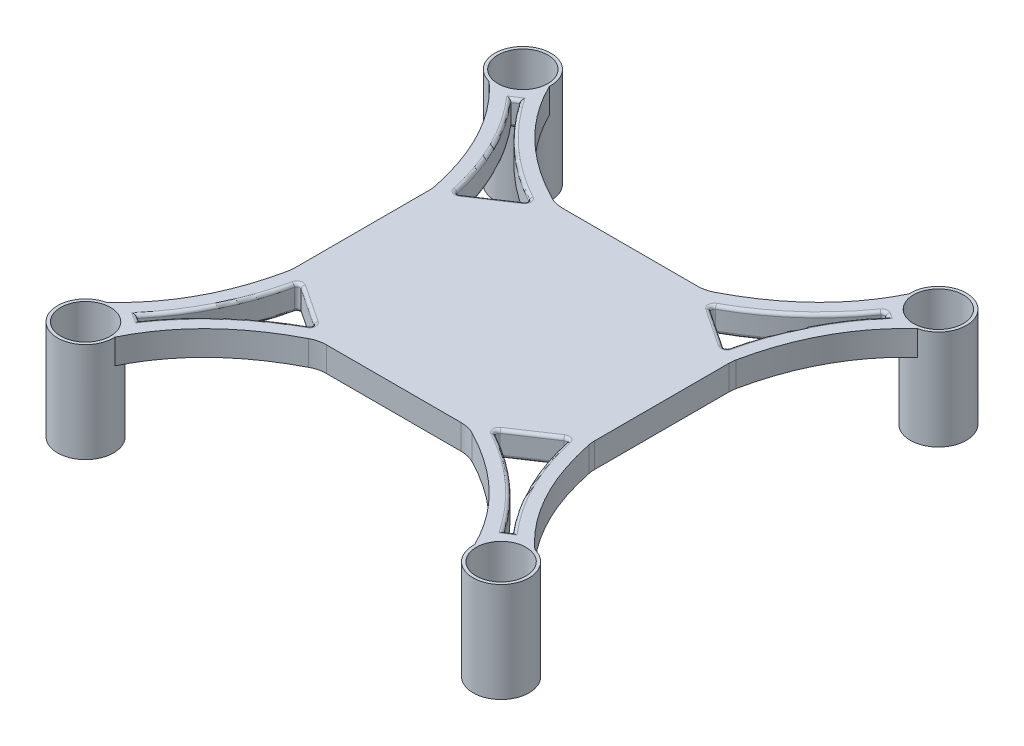
SolidWorks part; units mm, degrees
ref_plane "Front Plane" through (0, 0, 0) normal (0, 0, 1) x (1, 0, 0)
ref_plane "Top Plane" through (0, 0, 0) normal (0, 1, 0) x (1, 0, 0)
ref_plane "Right Plane" through (0, 0, 0) normal (1, 0, 0) x (0, 0, -1)
sketch "Sketch1" plane through (0, 0, 0) normal (0, 1, 0) x (1, 0, 0)
  line L0 (0, 48.6138) -> (0, -54.4719) construction
  line L1 (-10.8164, 24.6879) -> (10.8164, 24.6879)
  line L2 (46.7137, 5.7094) -> (-47.0237, 5.7094) construction
  line L3 (24.068, 16.5258) -> (24.068, -5.1069)
  line L4 (-10.8164, -13.269) -> (10.8164, -13.269)
  line L5 (-24.068, 16.5258) -> (-24.068, -5.1069)
  circle A0 centre (33.37, 40.8271) radius 4
  arc A1 (13.1162, 25.2482) -> (10.8164, 24.6879) centre (10.8164, 29.6879) cw
  arc A2 (24.1737, 17.5483) -> (24.068, 16.5258) centre (29.068, 16.5258) ccw
  arc A3 (24.1737, -6.1295) -> (24.068, -5.1069) centre (29.068, -5.1069) cw
  circle A4 centre (33.37, -29.4083) radius 4
  arc A5 (13.1162, -13.8293) -> (10.8164, -13.269) centre (10.8164, -18.269) ccw
  arc A6 (-13.1162, 25.2482) -> (-10.8164, 24.6879) centre (-10.8164, 29.6879) ccw
  arc A7 (-13.1162, -13.8293) -> (-10.8164, -13.269) centre (-10.8164, -18.269) cw
  circle A8 centre (-33.37, -29.4083) radius 4
  circle A9 centre (-33.37, 40.8271) radius 4
  arc A10 (-24.1737, 17.5483) -> (-24.068, 16.5258) centre (-29.068, 16.5258) cw
  arc A11 (-24.1737, -6.1295) -> (-24.068, -5.1069) centre (-29.068, -5.1069) ccw
  spline S0 degree 3 poles (13.1162, 25.2482) (17.1244, 27.3245) (23.8928, 32.2537) (28.1654, 38.7361) (29.6777, 42.3656) knots 0.037225 0.037225 0.037225 0.037225 0.443973 0.850721 0.850721 0.850721 0.850721
  spline S1 degree 3 poles (24.1737, 17.5483) (25.0548, 21.7657) (27.8837, 29.4488) (32.8158, 35.2456) (35.8785, 37.7115) knots 0.053222 0.053222 0.053222 0.053222 0.443973 0.850721 0.850721 0.850721 0.850721
  spline S2 degree 3 poles (24.1737, -6.1295) (25.0548, -10.3468) (27.8837, -18.0299) (32.8158, -23.8267) (35.8785, -26.2926) knots 0.053222 0.053222 0.053222 0.053222 0.443973 0.850721 0.850721 0.850721 0.850721
  spline S3 degree 3 poles (13.1162, -13.8293) (17.1244, -15.9056) (23.8928, -20.8348) (28.1654, -27.3172) (29.6777, -30.9467) knots 0.037225 0.037225 0.037225 0.037225 0.443973 0.850721 0.850721 0.850721 0.850721
  spline S4 degree 3 poles (-13.1162, -13.8293) (-17.1244, -15.9056) (-23.8928, -20.8348) (-28.1654, -27.3172) (-29.6777, -30.9467) knots 0.037225 0.037225 0.037225 0.037225 0.443973 0.850721 0.850721 0.850721 0.850721
  spline S5 degree 3 poles (-24.1737, -6.1295) (-25.0548, -10.3468) (-27.8837, -18.0299) (-32.8158, -23.8267) (-35.8785, -26.2926) knots 0.053222 0.053222 0.053222 0.053222 0.443973 0.850721 0.850721 0.850721 0.850721
  spline S6 degree 3 poles (-24.1737, 17.5483) (-25.0548, 21.7657) (-27.8837, 29.4488) (-32.8158, 35.2456) (-35.8785, 37.7115) knots 0.053222 0.053222 0.053222 0.053222 0.443973 0.850721 0.850721 0.850721 0.850721
  spline S7 degree 3 poles (-13.1162, 25.2482) (-17.1244, 27.3245) (-23.8928, 32.2537) (-28.1654, 38.7361) (-29.6777, 42.3656) knots 0.037225 0.037225 0.037225 0.037225 0.443973 0.850721 0.850721 0.850721 0.850721
  point P19 (24.068, 5.7094)
  point P37 (0, -13.269)
  point P54 (0, 24.6879)
  point P56 (0, 24.6879)
  dimension "D2" = 5
  dimension "D1" = 5
extrude "Boss-Extrude3" add sketch "Sketch1" along normal blind 4 contours A6 S7 A9 S6 A10 L5 A11 S5 A8 S4 A7 L4 A5 S3 A4 S2 A3 L3 A2 S1 A0 S0 A1 L1 | A4 | A8
sketch "Sketch5" plane through (0, 4, 0) normal (0, 1, 0) x (1, 0, 0)
  line L8 (30.1977, 35.734) -> (29.3225, 36.2906)
  line L9 (14.2661, 23.0284) -> (21.7265, 18.0596)
  line L10 (0, 31.6796) -> (0, -34.2074) construction
  line L11 (-56.7161, 5.7094) -> (61.3158, 5.7094) construction
  line L12 (-21.568, 16.5258) -> (-21.568, -5.1069)
  line L13 (-10.8164, -10.769) -> (10.8164, -10.769)
  line L14 (21.568, -5.1069) -> (21.568, 16.5258)
  line L15 (10.8164, 22.1879) -> (-10.8164, 22.1879)
  line L16 (-21.568, 16.5258) -> (-21.568, -5.1069)
  line L17 (-10.8164, -10.769) -> (10.8164, -10.769)
  line L18 (21.568, -5.1069) -> (21.568, 16.5258)
  line L19 (10.8164, 22.1879) -> (-10.8164, 22.1879)
  line L20 (-30.1977, 35.734) -> (-29.3225, 36.2906)
  line L21 (-14.2661, 23.0284) -> (-21.7265, 18.0596)
  line L22 (30.1977, -24.3151) -> (29.3225, -24.8718)
  line L23 (14.2661, -11.6095) -> (21.7265, -6.6407)
  line L24 (-14.2661, -11.6095) -> (-21.7265, -6.6407)
  line L25 (-30.1977, -24.3151) -> (-29.3225, -24.8718)
  arc A24 (21.7265, 18.0596) -> (30.1977, 35.734) centre (59.9069, 10.6274) cw
  arc A25 (14.2661, 23.0284) -> (29.3225, 36.2906) centre (-4.8209, 59.8754) ccw
  arc A26 (-14.2661, 23.0284) -> (-29.3225, 36.2906) centre (4.8209, 59.8754) cw
  arc A27 (-21.7265, 18.0596) -> (-30.1977, 35.734) centre (-59.9069, 10.6274) ccw
  arc A28 (21.7265, -6.6407) -> (30.1977, -24.3151) centre (59.9069, 0.7914) ccw
  arc A29 (14.2661, -11.6095) -> (29.3225, -24.8718) centre (-4.8209, -48.4565) cw
  arc A30 (-21.7265, -6.6407) -> (-30.1977, -24.3151) centre (-59.9069, 0.7914) cw
  arc A31 (-14.2661, -11.6095) -> (-29.3225, -24.8718) centre (4.8209, -48.4565) ccw
  arc A36 (-14.2661, 23.0284) -> (-10.8164, 22.1879) centre (-10.8164, 29.6879) ccw
  arc A37 (-31.9854, 41.404) -> (-34.3107, 39.6587) centre (-33.37, 40.8271) ccw
  arc A38 (-21.568, 16.5258) -> (-21.7265, 18.0596) centre (-29.068, 16.5258) ccw
  arc A39 (-21.7265, -6.6407) -> (-21.568, -5.1069) centre (-29.068, -5.1069) ccw
  arc A40 (-34.3107, -28.2399) -> (-31.9854, -29.9852) centre (-33.37, -29.4083) ccw
  arc A41 (-10.8164, -10.769) -> (-14.2661, -11.6095) centre (-10.8164, -18.269) ccw
  arc A42 (14.2661, -11.6095) -> (10.8164, -10.769) centre (10.8164, -18.269) ccw
  arc A43 (31.9854, -29.9852) -> (34.3107, -28.2399) centre (33.37, -29.4083) ccw
  arc A44 (21.568, -5.1069) -> (21.7265, -6.6407) centre (29.068, -5.1069) ccw
  arc A45 (21.7265, 18.0596) -> (21.568, 16.5258) centre (29.068, 16.5258) ccw
  arc A46 (34.3107, 39.6587) -> (31.9854, 41.404) centre (33.37, 40.8271) ccw
  arc A47 (10.8164, 22.1879) -> (14.2661, 23.0284) centre (10.8164, 29.6879) ccw
  arc A48 (-14.2661, 23.0284) -> (-10.8164, 22.1879) centre (-10.8164, 29.6879) ccw
  arc A49 (-31.9854, 41.404) -> (-34.3107, 39.6587) centre (-33.37, 40.8271) ccw
  arc A50 (-21.568, 16.5258) -> (-21.7265, 18.0596) centre (-29.068, 16.5258) ccw
  arc A51 (-21.7265, -6.6407) -> (-21.568, -5.1069) centre (-29.068, -5.1069) ccw
  arc A52 (-34.3107, -28.2399) -> (-31.9854, -29.9852) centre (-33.37, -29.4083) ccw
  arc A53 (-10.8164, -10.769) -> (-14.2661, -11.6095) centre (-10.8164, -18.269) ccw
  arc A54 (14.2661, -11.6095) -> (10.8164, -10.769) centre (10.8164, -18.269) ccw
  arc A55 (31.9854, -29.9852) -> (34.3107, -28.2399) centre (33.37, -29.4083) ccw
  arc A56 (21.568, -5.1069) -> (21.7265, -6.6407) centre (29.068, -5.1069) ccw
  arc A57 (21.7265, 18.0596) -> (21.568, 16.5258) centre (29.068, 16.5258) ccw
  arc A58 (34.3107, 39.6587) -> (31.9854, 41.404) centre (33.37, 40.8271) ccw
  arc A59 (10.8164, 22.1879) -> (14.2661, 23.0284) centre (10.8164, 29.6879) ccw
  spline S24 degree 3 poles (-1293.2283, -2676.1936) (402.9954, 283.6964) (71.687, -39.0407) (-20.733, 27.0608) (-21.5941, 27.7299) (-23.2451, 29.1291) (-24.0372, 29.8607) (-26.3082, 32.1572) (-27.6818, 33.823) (-29.5062, 36.5488) (-30.0686, 37.4862) (-148.6105, 258.9601) (2211.5543, 1795.9862) (-2829.0833, -598.5842) knots -12.641044 -12.641044 -12.641044 -12.641044 0.25 0.25 0.375 0.375 0.5 0.5 0.75 0.75 0.875 0.875 29.563011 29.563011 29.563011 29.563011 only from (-14.2661, 23.0284) to (-31.9854, 41.404)
  spline S25 degree 3 poles (184.4367, 1294.6818) (-2287.7745, -1535.7828) (-189.055, 223.3772) (-29.3932, 34.7953) (-29.0569, 34.3781) (-28.4081, 33.5326) (-28.0949, 33.1036) (-27.1878, 31.798) (-26.6265, 30.9032) (-25.5858, 29.0674) (-25.1064, 28.1263) (-24.2254, 26.2004) (-23.8232, 25.2138) (14.8609, -81.4612) (-389.7731, -313.9027) (2922.9923, 517.5478) knots -28.611005 -28.611005 -28.611005 -28.611005 0.25 0.25 0.3125 0.3125 0.375 0.375 0.5 0.5 0.625 0.625 0.75 0.75 13.911662 13.911662 13.911662 13.911662 only from (-34.3107, 39.6587) to (-21.7265, 18.0596)
  spline S26 degree 3 poles (2921.1119, -516.4542) (-391.9018, 328.5971) (14.9929, 93.228) (-23.8239, -13.7968) (-24.2273, -14.786) (-25.109, -16.7127) (-25.5883, -17.6532) (-27.1475, -20.403) (-28.3481, -22.1405) (-30.0728, -24.1795) (-30.4289, -24.5805) (-31.1575, -25.3621) (-31.5307, -25.7436) (-200.6034, -190.4869) (-2092.5502, 1439.1475) (1401.2137, -2538.0416) knots -12.9551 -12.9551 -12.9551 -12.9551 0.25 0.25 0.375 0.375 0.5 0.5 0.75 0.75 0.8125 0.8125 0.875 0.875 28.469753 28.469753 28.469753 28.469753 only from (-21.7265, -6.6407) to (-34.3107, -28.2399)
  spline S27 degree 3 poles (-1299.9106, -167.3195) (2099.0764, -1746.164) (-165.6783, -228.7682) (-28.6026, -23.7794) (-28.2872, -23.3321) (-27.6386, -22.4581) (-27.3048, -22.0305) (-26.2754, -20.7747) (-25.5522, -19.9738) (-24.0357, -18.4404) (-23.2425, -17.7079) (-21.5899, -16.3076) (-20.7278, -15.6381) (71.893, 50.5892) (405.3389, -272.9519) (-1299.2596, 2684.5757) knots -27.923103 -27.923103 -27.923103 -27.923103 0.25 0.25 0.3125 0.3125 0.375 0.375 0.5 0.5 0.625 0.625 0.75 0.75 13.681261 13.681261 13.681261 13.681261 only from (-31.9854, -29.9852) to (-14.2661, -11.6095)
  spline S28 degree 3 poles (1293.2283, 2687.6124) (-402.9954, -272.2775) (-71.687, 50.4595) (20.733, -15.6419) (21.5941, -16.311) (23.2451, -17.7102) (24.0372, -18.4419) (26.3082, -20.7383) (27.6818, -22.4042) (29.5062, -25.1299) (30.0686, -26.0673) (148.6105, -247.5412) (-2211.5543, -1784.5673) (2829.0833, 610.0031) knots -12.641044 -12.641044 -12.641044 -12.641044 0.25 0.25 0.375 0.375 0.5 0.5 0.75 0.75 0.875 0.875 29.563011 29.563011 29.563011 29.563011 only from (14.2661, -11.6095) to (31.9854, -29.9852)
  spline S29 degree 3 poles (-184.4367, -1283.2629) (2287.7745, 1547.2017) (189.055, -211.9583) (29.3932, -23.3765) (29.0569, -22.9592) (28.4081, -22.1137) (28.0949, -21.6847) (27.1878, -20.3792) (26.6265, -19.4843) (25.5858, -17.6485) (25.1064, -16.7074) (24.2254, -14.7815) (23.8232, -13.7949) (-14.8609, 92.88) (389.7731, 325.3216) (-2922.9923, -506.1289) knots -28.611005 -28.611005 -28.611005 -28.611005 0.25 0.25 0.3125 0.3125 0.375 0.375 0.5 0.5 0.625 0.625 0.75 0.75 13.911662 13.911662 13.911662 13.911662 only from (34.3107, -28.2399) to (21.7265, -6.6407)
  spline S30 degree 3 poles (-2921.1119, 527.8731) (391.9018, -317.1782) (-14.9929, -81.8091) (23.8239, 25.2157) (24.2273, 26.2049) (25.109, 28.1316) (25.5883, 29.0721) (27.1475, 31.8218) (28.3481, 33.5593) (30.0728, 35.5984) (30.4289, 35.9994) (31.1575, 36.781) (31.5307, 37.1625) (200.6034, 201.9057) (2092.5502, -1427.7286) (-1401.2137, 2549.4604) knots -12.9551 -12.9551 -12.9551 -12.9551 0.25 0.25 0.375 0.375 0.5 0.5 0.75 0.75 0.8125 0.8125 0.875 0.875 28.469753 28.469753 28.469753 28.469753 only from (21.7265, 18.0596) to (34.3107, 39.6587)
  spline S31 degree 3 poles (1299.9106, 178.7384) (-2099.0764, 1757.5829) (165.6783, 240.187) (28.6026, 35.1983) (28.2872, 34.7509) (27.6386, 33.877) (27.3048, 33.4493) (26.2754, 32.1936) (25.5522, 31.3927) (24.0357, 29.8593) (23.2425, 29.1267) (21.5899, 27.7265) (20.7278, 27.0569) (-71.893, -39.1703) (-405.3389, 284.3708) (1299.2596, -2673.1568) knots -27.923103 -27.923103 -27.923103 -27.923103 0.25 0.25 0.3125 0.3125 0.375 0.375 0.5 0.5 0.625 0.625 0.75 0.75 13.681261 13.681261 13.681261 13.681261 only from (31.9854, 41.404) to (14.2661, 23.0284)
  spline S32 degree 3 poles (-14.2661, 23.0284) (-16.205, 24.0327) (-18.0703, 25.1564) (-20.733, 27.0608) (-21.5941, 27.7299) (-23.2451, 29.1291) (-24.0372, 29.8607) (-26.3082, 32.1572) (-27.6818, 33.823) (-29.5062, 36.5488) (-30.0686, 37.4862) (-31.0971, 39.4078) (-31.5644, 40.3937) (-31.9854, 41.404) knots 0 0 0 0 0.25 0.25 0.375 0.375 0.5 0.5 0.75 0.75 0.875 0.875 1 1 1 1
  spline S33 degree 3 poles (-34.3107, 39.6587) (-32.6438, 38.3167) (-31.1183, 36.8328) (-29.3932, 34.7953) (-29.0569, 34.3781) (-28.4081, 33.5326) (-28.0949, 33.1036) (-27.1878, 31.798) (-26.6265, 30.9032) (-25.5858, 29.0674) (-25.1064, 28.1263) (-24.2254, 26.2004) (-23.8232, 25.2138) (-22.7314, 22.203) (-22.1633, 20.1501) (-21.7265, 18.0596) knots 0 0 0 0 0.25 0.25 0.3125 0.3125 0.375 0.375 0.5 0.5 0.625 0.625 0.75 0.75 1 1 1 1
  spline S34 degree 3 poles (-21.7265, -6.6407) (-22.1635, -8.7325) (-22.7319, -10.786) (-23.8239, -13.7968) (-24.2273, -14.786) (-25.109, -16.7127) (-25.5883, -17.6532) (-27.1475, -20.403) (-28.3481, -22.1405) (-30.0728, -24.1795) (-30.4289, -24.5805) (-31.1575, -25.3621) (-31.5307, -25.7436) (-32.677, -26.8605) (-33.4765, -27.5682) (-34.3107, -28.2399) knots 0 0 0 0 0.25 0.25 0.375 0.375 0.5 0.5 0.75 0.75 0.8125 0.8125 0.875 0.875 1 1 1 1
  spline S35 degree 3 poles (-31.9854, -29.9852) (-31.1443, -27.9665) (-30.1197, -26.0482) (-28.6026, -23.7794) (-28.2872, -23.3321) (-27.6386, -22.4581) (-27.3048, -22.0305) (-26.2754, -20.7747) (-25.5522, -19.9738) (-24.0357, -18.4404) (-23.2425, -17.7079) (-21.5899, -16.3076) (-20.7278, -15.6381) (-18.0676, -13.7359) (-16.2038, -12.6132) (-14.2661, -11.6095) knots 0 0 0 0 0.25 0.25 0.3125 0.3125 0.375 0.375 0.5 0.5 0.625 0.625 0.75 0.75 1 1 1 1
  spline S36 degree 3 poles (14.2661, -11.6095) (16.205, -12.6139) (18.0703, -13.7375) (20.733, -15.6419) (21.5941, -16.311) (23.2451, -17.7102) (24.0372, -18.4419) (26.3082, -20.7383) (27.6818, -22.4042) (29.5062, -25.1299) (30.0686, -26.0673) (31.0971, -27.989) (31.5644, -28.9748) (31.9854, -29.9852) knots 0 0 0 0 0.25 0.25 0.375 0.375 0.5 0.5 0.75 0.75 0.875 0.875 1 1 1 1
  spline S37 degree 3 poles (34.3107, -28.2399) (32.6438, -26.8979) (31.1183, -25.414) (29.3932, -23.3765) (29.0569, -22.9592) (28.4081, -22.1137) (28.0949, -21.6847) (27.1878, -20.3792) (26.6265, -19.4843) (25.5858, -17.6485) (25.1064, -16.7074) (24.2254, -14.7815) (23.8232, -13.7949) (22.7314, -10.7842) (22.1633, -8.7312) (21.7265, -6.6407) knots 0 0 0 0 0.25 0.25 0.3125 0.3125 0.375 0.375 0.5 0.5 0.625 0.625 0.75 0.75 1 1 1 1
  spline S38 degree 3 poles (21.7265, 18.0596) (22.1635, 20.1513) (22.7319, 22.2049) (23.8239, 25.2157) (24.2273, 26.2049) (25.109, 28.1316) (25.5883, 29.0721) (27.1475, 31.8218) (28.3481, 33.5593) (30.0728, 35.5984) (30.4289, 35.9994) (31.1575, 36.781) (31.5307, 37.1625) (32.677, 38.2793) (33.4765, 38.9871) (34.3107, 39.6587) knots 0 0 0 0 0.25 0.25 0.375 0.375 0.5 0.5 0.75 0.75 0.8125 0.8125 0.875 0.875 1 1 1 1
  spline S39 degree 3 poles (31.9854, 41.404) (31.1443, 39.3854) (30.1197, 37.467) (28.6026, 35.1983) (28.2872, 34.7509) (27.6386, 33.877) (27.3048, 33.4493) (26.2754, 32.1936) (25.5522, 31.3927) (24.0357, 29.8593) (23.2425, 29.1267) (21.5899, 27.7265) (20.7278, 27.0569) (18.0676, 25.1548) (16.2038, 24.0321) (14.2661, 23.0284) knots 0 0 0 0 0.25 0.25 0.3125 0.3125 0.375 0.375 0.5 0.5 0.625 0.625 0.75 0.75 1 1 1 1
  dimension "D2" = 6
  dimension "D1" = 2.5
extrude "Cut-Extrude3" cut sketch "Sketch5" against normal blind 4 contours A27 L20 A26 L21 | A31 L25 A30 L24 | A29 L22 A28 L23 | L9 A24 L8 A25
sketch "Sketch7" plane through (0, 4, 0) normal (0, 1, 0) x (1, 0, 0)
  line L0 (0, 39.7075) -> (0, -36.8004) construction
  line L1 (24.068, 5.7094) -> (-40.5042, 5.7094) construction
  line L4 (-24.068, 16.5258) -> (-24.068, -5.1069)
  line L5 (-10.8164, -13.269) -> (10.8164, -13.269)
  line L6 (24.068, -5.1069) -> (24.068, 16.5258)
  line L7 (10.8164, 24.6879) -> (-10.8164, 24.6879)
  line L8 (-24.068, 16.5258) -> (-24.068, -5.1069)
  line L9 (-10.8164, -13.269) -> (10.8164, -13.269)
  line L10 (24.068, -5.1069) -> (24.068, 16.5258)
  line L11 (10.8164, 24.6879) -> (-10.8164, 24.6879)
  circle A0 centre (33.37, 40.8271) radius 4.5
  circle A1 centre (-33.37, 40.8271) radius 4.5
  circle A2 centre (33.37, -29.4083) radius 4.5
  circle A3 centre (-33.37, -29.4083) radius 4.5
  arc A12 (-13.1162, 25.2482) -> (-10.8164, 24.6879) centre (-10.8164, 29.6879) ccw
  arc A13 (-29.6777, 42.3656) -> (-35.8785, 37.7115) centre (-33.37, 40.8271) ccw
  arc A14 (-24.068, 16.5258) -> (-24.1737, 17.5483) centre (-29.068, 16.5258) ccw
  arc A15 (-24.1737, -6.1295) -> (-24.068, -5.1069) centre (-29.068, -5.1069) ccw
  arc A16 (-35.8785, -26.2926) -> (-29.6777, -30.9467) centre (-33.37, -29.4083) ccw
  arc A17 (-10.8164, -13.269) -> (-13.1162, -13.8293) centre (-10.8164, -18.269) ccw
  arc A18 (13.1162, -13.8293) -> (10.8164, -13.269) centre (10.8164, -18.269) ccw
  arc A19 (29.6777, -30.9467) -> (35.8785, -26.2926) centre (33.37, -29.4083) ccw
  arc A20 (24.068, -5.1069) -> (24.1737, -6.1295) centre (29.068, -5.1069) ccw
  arc A21 (24.1737, 17.5483) -> (24.068, 16.5258) centre (29.068, 16.5258) ccw
  arc A22 (35.8785, 37.7115) -> (29.6777, 42.3656) centre (33.37, 40.8271) ccw
  arc A23 (10.8164, 24.6879) -> (13.1162, 25.2482) centre (10.8164, 29.6879) ccw
  arc A24 (-13.1162, 25.2482) -> (-10.8164, 24.6879) centre (-10.8164, 29.6879) ccw
  arc A26 (-24.068, 16.5258) -> (-24.1737, 17.5483) centre (-29.068, 16.5258) ccw
  arc A27 (-24.1737, -6.1295) -> (-24.068, -5.1069) centre (-29.068, -5.1069) ccw
  arc A29 (-10.8164, -13.269) -> (-13.1162, -13.8293) centre (-10.8164, -18.269) ccw
  arc A30 (13.1162, -13.8293) -> (10.8164, -13.269) centre (10.8164, -18.269) ccw
  arc A32 (24.068, -5.1069) -> (24.1737, -6.1295) centre (29.068, -5.1069) ccw
  arc A33 (24.1737, 17.5483) -> (24.068, 16.5258) centre (29.068, 16.5258) ccw
  arc A35 (10.8164, 24.6879) -> (13.1162, 25.2482) centre (10.8164, 29.6879) ccw
  spline S8 degree 3 poles (2720.72, 1244.7307) (991.1455, 333.5721) (-865.7115, -486.6483) (635.9303, 783.1648) (2262.5906, 1965.6024) knots -14.255308 -14.255308 -14.255308 -14.255308 0.443973 15.5857 15.5857 15.5857 15.5857 only from (-13.1162, 25.2482) to (-29.6777, 42.3656)
  spline S9 degree 3 poles (-2522.8628, -1626.2016) (-933.1195, -394.5106) (705.5357, 692.6861) (-600.5192, -861.0366) (-1958.2843, -2267.0883) knots -14.68191 -14.68191 -14.68191 -14.68191 0.45997 15.158154 15.158154 15.158154 15.158154 only from (-35.8785, 37.7115) to (-24.1737, 17.5483)
  spline S10 degree 3 poles (-1958.2964, 2278.5196) (-600.523, 872.46) (705.5374, -681.2679) (-933.1178, 405.9283) (-2522.8577, 1637.6166) knots -14.254254 -14.254254 -14.254254 -14.254254 0.443973 15.585837 15.585837 15.585837 15.585837 only from (-24.1737, -6.1295) to (-35.8785, -26.2926)
  spline S11 degree 3 poles (2262.6173, -1954.203) (635.9387, -771.753) (-865.7103, 498.064) (991.1298, -322.1462) (2720.6752, -1233.2882) knots -14.697836 -14.697836 -14.697836 -14.697836 0.443973 15.143128 15.143128 15.143128 15.143128 only from (-29.6777, -30.9467) to (-13.1162, -13.8293)
  spline S12 degree 3 poles (-2720.72, -1233.3118) (-991.1455, -322.1532) (865.7115, 498.0671) (-635.9303, -771.746) (-2262.5906, -1954.1835) knots -14.255308 -14.255308 -14.255308 -14.255308 0.443973 15.5857 15.5857 15.5857 15.5857 only from (13.1162, -13.8293) to (29.6777, -30.9467)
  spline S13 degree 3 poles (2522.8628, 1637.6205) (933.1195, 405.9294) (-705.5357, -681.2672) (600.5192, 872.4554) (1958.2843, 2278.5072) knots -14.68191 -14.68191 -14.68191 -14.68191 0.45997 15.158154 15.158154 15.158154 15.158154 only from (35.8785, -26.2926) to (24.1737, -6.1295)
  spline S14 degree 3 poles (1958.2964, -2267.1008) (600.523, -861.0411) (-705.5374, 692.6868) (933.1178, -394.5094) (2522.8577, -1626.1977) knots -14.254254 -14.254254 -14.254254 -14.254254 0.443973 15.585837 15.585837 15.585837 15.585837 only from (24.1737, 17.5483) to (35.8785, 37.7115)
  spline S15 degree 3 poles (-2262.6173, 1965.6218) (-635.9387, 783.1719) (865.7103, -486.6451) (-991.1298, 333.5651) (-2720.6752, 1244.7071) knots -14.697836 -14.697836 -14.697836 -14.697836 0.443973 15.143128 15.143128 15.143128 15.143128 only from (29.6777, 42.3656) to (13.1162, 25.2482)
  spline S16 degree 3 poles (-13.1162, 25.2482) (-17.1244, 27.3245) (-23.8928, 32.2537) (-28.1654, 38.7361) (-29.6777, 42.3656) knots 0.037225 0.037225 0.037225 0.037225 0.443973 0.850721 0.850721 0.850721 0.850721
  spline S17 degree 3 poles (-35.8785, 37.7115) (-32.8158, 35.2456) (-27.8837, 29.4488) (-25.0548, 21.7657) (-24.1737, 17.5483) knots 0.053222 0.053222 0.053222 0.053222 0.45997 0.850721 0.850721 0.850721 0.850721
  spline S18 degree 3 poles (-24.1737, -6.1295) (-25.0548, -10.3468) (-27.8837, -18.0299) (-32.8158, -23.8267) (-35.8785, -26.2926) knots 0.053222 0.053222 0.053222 0.053222 0.443973 0.850721 0.850721 0.850721 0.850721
  spline S19 degree 3 poles (-29.6777, -30.9467) (-28.1654, -27.3172) (-23.8928, -20.8348) (-17.1244, -15.9056) (-13.1162, -13.8293) knots 0.037225 0.037225 0.037225 0.037225 0.443973 0.850721 0.850721 0.850721 0.850721
  spline S20 degree 3 poles (13.1162, -13.8293) (17.1244, -15.9056) (23.8928, -20.8348) (28.1654, -27.3172) (29.6777, -30.9467) knots 0.037225 0.037225 0.037225 0.037225 0.443973 0.850721 0.850721 0.850721 0.850721
  spline S21 degree 3 poles (35.8785, -26.2926) (32.8158, -23.8267) (27.8837, -18.0299) (25.0548, -10.3468) (24.1737, -6.1295) knots 0.053222 0.053222 0.053222 0.053222 0.45997 0.850721 0.850721 0.850721 0.850721
  spline S22 degree 3 poles (24.1737, 17.5483) (25.0548, 21.7657) (27.8837, 29.4488) (32.8158, 35.2456) (35.8785, 37.7115) knots 0.053222 0.053222 0.053222 0.053222 0.443973 0.850721 0.850721 0.850721 0.850721
  spline S23 degree 3 poles (29.6777, 42.3656) (28.1654, 38.7361) (23.8928, 32.2537) (17.1244, 27.3245) (13.1162, 25.2482) knots 0.037225 0.037225 0.037225 0.037225 0.443973 0.850721 0.850721 0.850721 0.850721
  dimension "D1" = 0
extrude "Cut-Extrude5" cut sketch "Sketch7" against normal blind 4 contours A0 | A2 | A3 | A1
sketch "Sketch9" plane through (0, 4, 0) normal (0, 1, 0) x (1, 0, 0)
  line L0 (0, 27.8112) -> (0, -19.6156) construction
  line L1 (-24.068, 5.7094) -> (24.068, 5.7094) construction
  line L4 (24.068, -5.1069) -> (24.068, 16.5258)
  line L5 (10.8164, 24.6879) -> (-10.8164, 24.6879)
  line L6 (-24.068, 16.5258) -> (-24.068, -5.1069)
  line L7 (-10.8164, -13.269) -> (10.8164, -13.269)
  line L8 (24.068, -5.1069) -> (24.068, 16.5258)
  line L9 (10.8164, 24.6879) -> (-10.8164, 24.6879)
  line L10 (-24.068, 16.5258) -> (-24.068, -5.1069)
  line L11 (-10.8164, -13.269) -> (10.8164, -13.269)
  circle A0 centre (33.37, 40.8271) radius 4.5
  circle A1 centre (-33.37, 40.8271) radius 4.5
  circle A2 centre (33.37, -29.4083) radius 4.5
  circle A3 centre (-33.37, -29.4083) radius 4.5
  arc A12 (34.4034, -25.0285) -> (28.8759, -29.1773) centre (33.37, -29.4083) ccw
  arc A13 (24.068, -5.1069) -> (24.1737, -6.1295) centre (29.068, -5.1069) ccw
  arc A14 (24.1737, 17.5483) -> (24.068, 16.5258) centre (29.068, 16.5258) ccw
  arc A15 (28.8759, 40.5962) -> (34.4034, 36.4474) centre (33.37, 40.8271) ccw
  arc A16 (10.8164, 24.6879) -> (13.1162, 25.2482) centre (10.8164, 29.6879) ccw
  arc A17 (-13.1162, 25.2482) -> (-10.8164, 24.6879) centre (-10.8164, 29.6879) ccw
  arc A18 (-34.4034, 36.4474) -> (-28.8759, 40.5962) centre (-33.37, 40.8271) ccw
  arc A19 (-24.068, 16.5258) -> (-24.1737, 17.5483) centre (-29.068, 16.5258) ccw
  arc A20 (-24.1737, -6.1295) -> (-24.068, -5.1069) centre (-29.068, -5.1069) ccw
  arc A21 (-28.8759, -29.1773) -> (-34.4034, -25.0285) centre (-33.37, -29.4083) ccw
  arc A22 (-10.8164, -13.269) -> (-13.1162, -13.8293) centre (-10.8164, -18.269) ccw
  arc A23 (13.1162, -13.8293) -> (10.8164, -13.269) centre (10.8164, -18.269) ccw
  arc A24 (34.4034, -25.0285) -> (28.8759, -29.1773) centre (33.37, -29.4083) ccw
  arc A25 (24.068, -5.1069) -> (24.1737, -6.1295) centre (29.068, -5.1069) ccw
  arc A26 (24.1737, 17.5483) -> (24.068, 16.5258) centre (29.068, 16.5258) ccw
  arc A27 (28.8759, 40.5962) -> (34.4034, 36.4474) centre (33.37, 40.8271) ccw
  arc A28 (10.8164, 24.6879) -> (13.1162, 25.2482) centre (10.8164, 29.6879) ccw
  arc A29 (-13.1162, 25.2482) -> (-10.8164, 24.6879) centre (-10.8164, 29.6879) ccw
  arc A30 (-34.4034, 36.4474) -> (-28.8759, 40.5962) centre (-33.37, 40.8271) ccw
  arc A31 (-24.068, 16.5258) -> (-24.1737, 17.5483) centre (-29.068, 16.5258) ccw
  arc A32 (-24.1737, -6.1295) -> (-24.068, -5.1069) centre (-29.068, -5.1069) ccw
  arc A33 (-28.8759, -29.1773) -> (-34.4034, -25.0285) centre (-33.37, -29.4083) ccw
  arc A34 (-10.8164, -13.269) -> (-13.1162, -13.8293) centre (-10.8164, -18.269) ccw
  arc A35 (13.1162, -13.8293) -> (10.8164, -13.269) centre (10.8164, -18.269) ccw
  spline S8 degree 3 poles (-5357.2757, -2664.1702) (-1912.2513, -755.434) (1713.0976, 1025.3533) (-1409.4863, -1393.1775) (-4710.1146, -3687.3644) knots -20.481796 -20.481796 -20.481796 -20.481796 0.443973 21.81683 21.81683 21.81683 21.81683 only from (13.1162, -13.8293) to (28.8759, -29.1773)
  spline S9 degree 3 poles (4870.7441, 3503.7181) (1745.9021, 975.1515) (-1448.5159, -1347.6569) (1273.7999, 1635.8688) (4068.5259, 4410.4332) knots -20.980454 -20.980454 -20.980454 -20.980454 0.392682 21.317512 21.317512 21.317512 21.317512 only from (34.4034, -25.0285) to (24.1737, -6.1295)
  spline S10 degree 3 poles (4068.6562, -4399.1437) (1273.8418, -1624.4958) (-1448.5206, 1359.0719) (1745.8553, -963.6987) (4870.6084, -3492.1894) knots -20.481182 -20.481182 -20.481182 -20.481182 0.443973 21.8168 21.8168 21.8168 21.8168 only from (24.1737, 17.5483) to (34.4034, 36.4474)
  spline S11 degree 3 poles (-4710.1672, 3698.8198) (-1409.5031, 1404.6094) (1713.0992, -1013.933) (-1912.2325, 766.8437) (-5357.2216, 2675.5592) knots -20.996285 -20.996285 -20.996285 -20.996285 0.376685 21.302345 21.302345 21.302345 21.302345 only from (28.8759, 40.5962) to (13.1162, 25.2482)
  spline S12 degree 3 poles (5357.2757, 2675.5891) (1912.2513, 766.8529) (-1713.0976, -1013.9344) (1409.4863, 1404.5964) (4710.1146, 3698.7833) knots -20.481796 -20.481796 -20.481796 -20.481796 0.443973 21.81683 21.81683 21.81683 21.81683 only from (-13.1162, 25.2482) to (-28.8759, 40.5962)
  spline S13 degree 3 poles (-4870.7441, -3492.2992) (-1745.9021, -963.7327) (1448.5159, 1359.0758) (-1273.7999, -1624.4499) (-4068.5259, -4399.0143) knots -20.980454 -20.980454 -20.980454 -20.980454 0.392682 21.317512 21.317512 21.317512 21.317512 only from (-34.4034, 36.4474) to (-24.1737, 17.5483)
  spline S14 degree 3 poles (-4068.6562, 4410.5626) (-1273.8418, 1635.9147) (1448.5206, -1347.653) (-1745.8553, 975.1176) (-4870.6084, 3503.6083) knots -20.481182 -20.481182 -20.481182 -20.481182 0.443973 21.8168 21.8168 21.8168 21.8168 only from (-24.1737, -6.1295) to (-34.4034, -25.0285)
  spline S15 degree 3 poles (4710.1672, -3687.4009) (1409.5031, -1393.1905) (-1713.0992, 1025.3518) (1912.2325, -755.4248) (5357.2216, -2664.1403) knots -20.996285 -20.996285 -20.996285 -20.996285 0.376685 21.302345 21.302345 21.302345 21.302345 only from (-28.8759, -29.1773) to (-13.1162, -13.8293)
  spline S16 degree 3 poles (13.1162, -13.8293) (17.1244, -15.9056) (23.333, -20.4271) (27.4415, -26.2554) (28.8759, -29.1773) knots 0.037225 0.037225 0.037225 0.037225 0.443973 0.783433 0.783433 0.783433 0.783433
  spline S17 degree 3 poles (34.4034, -25.0285) (31.9985, -22.8351) (27.645, -17.3817) (25.0548, -10.3468) (24.1737, -6.1295) knots 0.053222 0.053222 0.053222 0.053222 0.392682 0.783433 0.783433 0.783433 0.783433
  spline S18 degree 3 poles (24.1737, 17.5483) (25.0548, 21.7657) (27.645, 28.8006) (31.9985, 34.254) (34.4034, 36.4474) knots 0.053222 0.053222 0.053222 0.053222 0.443973 0.783433 0.783433 0.783433 0.783433
  spline S19 degree 3 poles (28.8759, 40.5962) (27.4415, 37.6743) (23.333, 31.8459) (17.1244, 27.3245) (13.1162, 25.2482) knots 0.037225 0.037225 0.037225 0.037225 0.376685 0.783433 0.783433 0.783433 0.783433
  spline S20 degree 3 poles (-13.1162, 25.2482) (-17.1244, 27.3245) (-23.333, 31.8459) (-27.4415, 37.6743) (-28.8759, 40.5962) knots 0.037225 0.037225 0.037225 0.037225 0.443973 0.783433 0.783433 0.783433 0.783433
  spline S21 degree 3 poles (-34.4034, 36.4474) (-31.9985, 34.254) (-27.645, 28.8006) (-25.0548, 21.7657) (-24.1737, 17.5483) knots 0.053222 0.053222 0.053222 0.053222 0.392682 0.783433 0.783433 0.783433 0.783433
  spline S22 degree 3 poles (-24.1737, -6.1295) (-25.0548, -10.3468) (-27.645, -17.3817) (-31.9985, -22.8351) (-34.4034, -25.0285) knots 0.053222 0.053222 0.053222 0.053222 0.443973 0.783433 0.783433 0.783433 0.783433
  spline S23 degree 3 poles (-28.8759, -29.1773) (-27.4415, -26.2554) (-23.333, -20.4271) (-17.1244, -15.9056) (-13.1162, -13.8293) knots 0.037225 0.037225 0.037225 0.037225 0.376685 0.783433 0.783433 0.783433 0.783433
  dimension "D1" = 0
extrude "Boss-Extrude4" add sketch "Sketch9" against normal blind 16 contours A0 | A3 | A2 | A1
sketch "Sketch10" plane through (0, 4, 0) normal (0, 1, 0) x (1, 0, 0)
  line L0 (0, 38.5683) -> (0, -35.8055) construction
  line L1 (-24.068, 5.7094) -> (24.068, 5.7094) construction
  line L4 (24.068, -5.1069) -> (24.068, 16.5258)
  line L5 (10.8164, 24.6879) -> (-10.8164, 24.6879)
  line L6 (-24.068, 16.5258) -> (-24.068, -5.1069)
  line L7 (-10.8164, -13.269) -> (10.8164, -13.269)
  line L8 (24.068, -5.1069) -> (24.068, 16.5258)
  line L9 (10.8164, 24.6879) -> (-10.8164, 24.6879)
  line L10 (-24.068, 16.5258) -> (-24.068, -5.1069)
  line L11 (-10.8164, -13.269) -> (10.8164, -13.269)
  circle A0 centre (33.37, 40.8271) radius 4
  circle A1 centre (-33.37, 40.8271) radius 4
  circle A2 centre (33.37, -29.4083) radius 4
  circle A3 centre (-33.37, -29.4083) radius 4
  arc A12 (28.8759, -29.1773) -> (34.4034, -25.0285) centre (33.37, -29.4083) ccw
  arc A13 (24.068, -5.1069) -> (24.1737, -6.1295) centre (29.068, -5.1069) ccw
  arc A14 (24.1737, 17.5483) -> (24.068, 16.5258) centre (29.068, 16.5258) ccw
  arc A15 (34.4034, 36.4474) -> (28.8759, 40.5962) centre (33.37, 40.8271) ccw
  arc A16 (10.8164, 24.6879) -> (13.1162, 25.2482) centre (10.8164, 29.6879) ccw
  arc A17 (-13.1162, 25.2482) -> (-10.8164, 24.6879) centre (-10.8164, 29.6879) ccw
  arc A18 (-28.8759, 40.5962) -> (-34.4034, 36.4474) centre (-33.37, 40.8271) ccw
  arc A19 (-24.068, 16.5258) -> (-24.1737, 17.5483) centre (-29.068, 16.5258) ccw
  arc A20 (-24.1737, -6.1295) -> (-24.068, -5.1069) centre (-29.068, -5.1069) ccw
  arc A21 (-34.4034, -25.0285) -> (-28.8759, -29.1773) centre (-33.37, -29.4083) ccw
  arc A22 (-10.8164, -13.269) -> (-13.1162, -13.8293) centre (-10.8164, -18.269) ccw
  arc A23 (13.1162, -13.8293) -> (10.8164, -13.269) centre (10.8164, -18.269) ccw
  arc A24 (28.8759, -29.1773) -> (34.4034, -25.0285) centre (33.37, -29.4083) ccw
  arc A25 (24.068, -5.1069) -> (24.1737, -6.1295) centre (29.068, -5.1069) ccw
  arc A26 (24.1737, 17.5483) -> (24.068, 16.5258) centre (29.068, 16.5258) ccw
  arc A27 (34.4034, 36.4474) -> (28.8759, 40.5962) centre (33.37, 40.8271) ccw
  arc A28 (10.8164, 24.6879) -> (13.1162, 25.2482) centre (10.8164, 29.6879) ccw
  arc A29 (-13.1162, 25.2482) -> (-10.8164, 24.6879) centre (-10.8164, 29.6879) ccw
  arc A30 (-28.8759, 40.5962) -> (-34.4034, 36.4474) centre (-33.37, 40.8271) ccw
  arc A31 (-24.068, 16.5258) -> (-24.1737, 17.5483) centre (-29.068, 16.5258) ccw
  arc A32 (-24.1737, -6.1295) -> (-24.068, -5.1069) centre (-29.068, -5.1069) ccw
  arc A33 (-34.4034, -25.0285) -> (-28.8759, -29.1773) centre (-33.37, -29.4083) ccw
  arc A34 (-10.8164, -13.269) -> (-13.1162, -13.8293) centre (-10.8164, -18.269) ccw
  arc A35 (13.1162, -13.8293) -> (10.8164, -13.269) centre (10.8164, -18.269) ccw
  spline S8 degree 3 poles (-2720.6991, -1233.3008) (-991.1382, -322.15) (865.6056, 498.0192) (-635.764, -771.6053) (-2262.0578, -1953.7963) knots -14.255249 -14.255249 -14.255249 -14.255249 0.443973 15.584047 15.584047 15.584047 15.584047 only from (13.1162, -13.8293) to (28.8759, -29.1773)
  spline S9 degree 3 poles (2522.2992, 1637.1839) (932.923, 405.7991) (-705.4608, -681.1763) (600.5246, 872.4619) (1958.3014, 2278.5249) knots -14.747408 -14.747408 -14.747408 -14.747408 0.392682 15.090928 15.090928 15.090928 15.090928 only from (34.4034, -25.0285) to (24.1737, -6.1295)
  spline S10 degree 3 poles (1958.2819, -2267.0858) (600.5184, -861.0357) (-705.452, 692.5868) (932.9108, -394.3721) (2522.2641, -1625.7378) knots -14.254202 -14.254202 -14.254202 -14.254202 0.443973 15.583952 15.583952 15.583952 15.583952 only from (24.1737, 17.5483) to (34.4034, 36.4474)
  spline S11 degree 3 poles (-2262.0339, 1965.1978) (-635.7565, 783.0178) (865.5972, -486.5951) (-991.1288, 333.5647) (-2720.6725, 1244.7057) knots -14.763314 -14.763314 -14.763314 -14.763314 0.376685 15.075832 15.075832 15.075832 15.075832 only from (28.8759, 40.5962) to (13.1162, 25.2482)
  spline S12 degree 3 poles (2720.6991, 1244.7197) (991.1382, 333.5688) (-865.6056, -486.6003) (635.764, 783.0242) (2262.0578, 1965.2151) knots -14.255249 -14.255249 -14.255249 -14.255249 0.443973 15.584047 15.584047 15.584047 15.584047 only from (-13.1162, 25.2482) to (-28.8759, 40.5962)
  spline S13 degree 3 poles (-2522.2992, -1625.765) (-932.923, -394.3802) (705.4608, 692.5951) (-600.5246, -861.043) (-1958.3014, -2267.106) knots -14.747408 -14.747408 -14.747408 -14.747408 0.392682 15.090928 15.090928 15.090928 15.090928 only from (-34.4034, 36.4474) to (-24.1737, 17.5483)
  spline S14 degree 3 poles (-1958.2819, 2278.5047) (-600.5184, 872.4545) (705.452, -681.1679) (-932.9108, 405.791) (-2522.2641, 1637.1567) knots -14.254202 -14.254202 -14.254202 -14.254202 0.443973 15.583952 15.583952 15.583952 15.583952 only from (-24.1737, -6.1295) to (-34.4034, -25.0285)
  spline S15 degree 3 poles (2262.0339, -1953.7789) (635.7565, -771.599) (-865.5972, 498.0139) (991.1288, -322.1458) (2720.6725, -1233.2868) knots -14.763314 -14.763314 -14.763314 -14.763314 0.376685 15.075832 15.075832 15.075832 15.075832 only from (-28.8759, -29.1773) to (-13.1162, -13.8293)
  spline S16 degree 3 poles (13.1162, -13.8293) (17.1244, -15.9056) (23.333, -20.4271) (27.4415, -26.2554) (28.8759, -29.1773) knots 0.037225 0.037225 0.037225 0.037225 0.443973 0.783433 0.783433 0.783433 0.783433
  spline S17 degree 3 poles (34.4034, -25.0285) (31.9985, -22.8351) (27.645, -17.3817) (25.0548, -10.3468) (24.1737, -6.1295) knots 0.053222 0.053222 0.053222 0.053222 0.392682 0.783433 0.783433 0.783433 0.783433
  spline S18 degree 3 poles (24.1737, 17.5483) (25.0548, 21.7657) (27.645, 28.8006) (31.9985, 34.254) (34.4034, 36.4474) knots 0.053222 0.053222 0.053222 0.053222 0.443973 0.783433 0.783433 0.783433 0.783433
  spline S19 degree 3 poles (28.8759, 40.5962) (27.4415, 37.6743) (23.333, 31.8459) (17.1244, 27.3245) (13.1162, 25.2482) knots 0.037225 0.037225 0.037225 0.037225 0.376685 0.783433 0.783433 0.783433 0.783433
  spline S20 degree 3 poles (-13.1162, 25.2482) (-17.1244, 27.3245) (-23.333, 31.8459) (-27.4415, 37.6743) (-28.8759, 40.5962) knots 0.037225 0.037225 0.037225 0.037225 0.443973 0.783433 0.783433 0.783433 0.783433
  spline S21 degree 3 poles (-34.4034, 36.4474) (-31.9985, 34.254) (-27.645, 28.8006) (-25.0548, 21.7657) (-24.1737, 17.5483) knots 0.053222 0.053222 0.053222 0.053222 0.392682 0.783433 0.783433 0.783433 0.783433
  spline S22 degree 3 poles (-24.1737, -6.1295) (-25.0548, -10.3468) (-27.645, -17.3817) (-31.9985, -22.8351) (-34.4034, -25.0285) knots 0.053222 0.053222 0.053222 0.053222 0.443973 0.783433 0.783433 0.783433 0.783433
  spline S23 degree 3 poles (-28.8759, -29.1773) (-27.4415, -26.2554) (-23.333, -20.4271) (-17.1244, -15.9056) (-13.1162, -13.8293) knots 0.037225 0.037225 0.037225 0.037225 0.376685 0.783433 0.783433 0.783433 0.783433
  dimension "D1" = 0
extrude "Cut-Extrude6" cut sketch "Sketch10" against normal blind 16 contours A0 | A2 | A3 | A1
fillet "Fillet1" radius 0.5 41 edges at (-22.6079, 0, 17.3169) (-24.8306, 0, 16.0202) (17.9963, 0, -20.544) (22.6079, 0, 17.3169) (29.3225, 2, -36.2906) (22.6079, 0, -28.7358) (14.2661, 2, -23.0284) (22.6079, 4, -28.7358) (-29.7601, 0, 24.5935) (-29.7601, 4, 24.5935) (-17.9963, 0, 9.1251) (-14.2661, 2, 11.6095) (-21.7265, 2, 6.6407) (-22.6079, 4, 17.3169) (-24.8306, 4, 16.0202) (-17.9963, 4, 9.1251) (-14.2661, 2, -23.0284) (-21.7265, 2, -18.0596) (21.7265, 2, -18.0596) (-29.7601, 0, -36.0123) (-29.7601, 4, -36.0123) (-24.8306, 4, -27.4391) (-24.8306, 0, -27.4391) (-17.9963, 0, -20.544) (-22.6079, 0, -28.7358) (-17.9963, 4, -20.544) (-22.6079, 4, -28.7358) (17.9963, 4, -20.544) (24.8306, 0, -27.4391) (24.8306, 4, -27.4391) (29.7601, 0, -36.0123) (29.7601, 4, -36.0123) (29.7601, 0, 24.5935) (29.7601, 4, 24.5935) (24.8306, 0, 16.0202) (21.7265, 2, 6.6407) (14.2661, 2, 11.6095) (22.6079, 4, 17.3169) (24.8306, 4, 16.0202) (17.9963, 0, 9.1251) (17.9963, 4, 9.1251)
